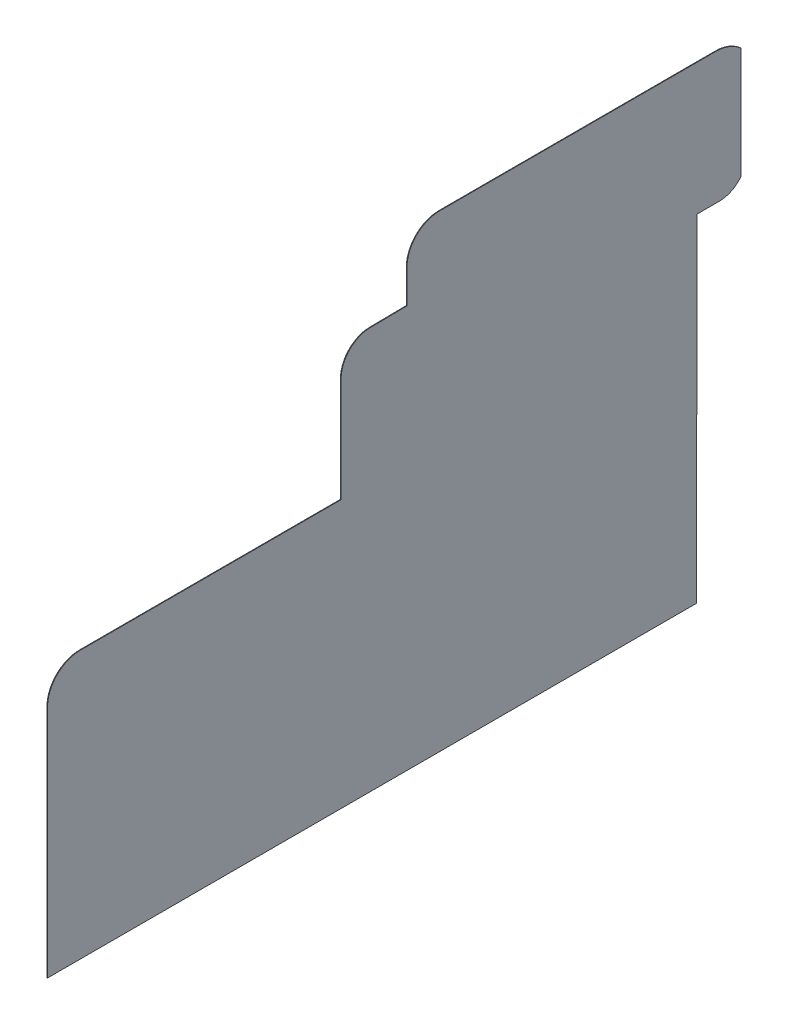
SolidWorks part; units mm, degrees
ref_plane "Piano frontale" through (0, 0, 0) normal (0, 0, 1) x (1, 0, 0)
ref_plane "Piano superiore" through (0, 0, 0) normal (0, 1, 0) x (1, 0, 0)
ref_plane "Piano destro" through (0, 0, 0) normal (1, 0, 0) x (0, 0, -1)
other "Grafica1"
other "Grafica (Chiusa) -1"
other "Grafica (Chiusa) -2"
other "Grafica (Chiusa) -3"
other "Grafica (Chiusa) -4"
other "Grafica (Chiusa) -5"
other "Grafica (Chiusa) -6"
sketch "Schizzo1" plane through (0, 0, 0) normal (1, 0, 0) x (0, 0, -1)
  line L0 (-1.1205, 0.0161) -> (-1.1205, 0.3954)
  line L1 (-1.0676, 0.4483) -> (-0.6462, 0.4483)
  line L2 (-0.6462, 0.6176) -> (-0.6462, 0.4483)
  line L3 (-0.5988, 0.6655) -> (-0.5398, 0.6662)
  line L4 (-0.5398, 0.6662) -> (-0.5398, 0.7202)
  line L5 (-0.4872, 0.7727) -> (-0.0411, 0.7727)
  line L6 (0, 0.7568) -> (0, 0.5776)
  line L7 (-0.0351, 0.5602) -> (-0.0712, 0.5602)
  line L8 (-0.0712, 0.5602) -> (-0.072, 0.0161)
  line L9 (-1.1205, 0.0161) -> (-0.072, 0.0161)
  arc A0 (-1.0676, 0.4483) -> (-1.1205, 0.3954) centre (-1.0676, 0.3954) ccw
  arc A1 (-0.5988, 0.6655) -> (-0.6462, 0.6176) centre (-0.5983, 0.6176) ccw
  arc A2 (-0.4872, 0.7727) -> (-0.5398, 0.7202) centre (-0.4872, 0.7202) ccw
  arc A3 (-0.0411, 0.7727) -> (0, 0.7568) centre (-0.0411, 0.7117) cw
  arc A4 (-0.0351, 0.5602) -> (0, 0.5776) centre (-0.0351, 0.6045) ccw
  point P0 (-1.0676, 0.4483)
  point P1 (-0.5988, 0.6655)
  point P4 (0, 0)
  point P5 (-0.5398, 0.6662)
  point P7 (-0.5398, 0.7202)
  point P8 (-0.4872, 0.7727)
  point P9 (-0.0411, 0.7727)
  point P11 (0, 0.7568)
  point P13 (0, 0.5776)
  point P16 (-0.0351, 0.5602)
  point P17 (-0.0712, 0.5602)
  point P19 (-0.072, 0.0161)
  point P21 (-1.1205, 0.0161)
  point P23 (-1.1205, 0.3954)
  point P41 (0, 0)
  dimension "D1" = 0.0529
  dimension "D4" = 0.0479
  dimension "D6" = 0.0525
  dimension "D2" = 0.3793
  dimension "D3" = 0.4214
  dimension "D5" = 0.0591
  dimension "D7" = 0.682
  dimension "D8" = 0.1064
  dimension "D9" = 0.6015
extrude "Estrusione-Estrusione1" add sketch "Schizzo1" along normal blind 0.001
